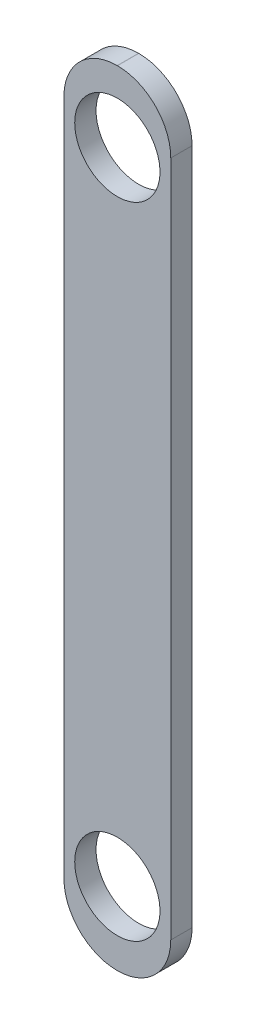
SolidWorks part; units mm, degrees
ref_plane "前视基准面" through (0, 0, 0) normal (0, 0, 1) x (1, 0, 0)
ref_plane "上视基准面" through (0, 0, 0) normal (0, 1, 0) x (1, 0, 0)
ref_plane "右视基准面" through (0, 0, 0) normal (1, 0, 0) x (0, 0, -1)
sketch "草图1" plane through (0, 0, 0) normal (0, 0, 1) x (1, 0, 0)
  line L1 (12.5298, -91.9211) -> (-12.5298, -91.9211)
  line L2 (12.5298, -91.9211) -> (12.5298, 91.9211)
  line L3 (12.5298, 91.9211) -> (-12.5298, 91.9211)
  line L4 (-12.5298, -91.9211) -> (-12.5298, 91.9211)
  line L5 (12.5298, -91.9211) -> (-12.5298, 91.9211) construction
  line L6 (12.5298, 91.9211) -> (-12.5298, -91.9211) construction
  point P0 (0, 0)
extrude "凸台-拉伸1" add sketch "草图1" along normal blind 5
sketch "草图2" plane through (0, 0, 0) normal (0, 0, -1) x (-1, 0, 0)
  circle A0 centre (0, 75.3125) radius 10
  circle A1 centre (0, -74.807) radius 10
  point P4 (0, -74.807)
  point P5 (0, 75.3125)
extrude "切除-拉伸1" cut sketch "草图2" against normal blind 5 contours A1 | A0
fillet "圆角1" radius 12.5 4 edges at (-12.5298, -91.9211, 2.5) (12.5298, -91.9211, 2.5) (12.5298, 91.9211, 2.5) (-12.5298, 91.9211, 2.5)
